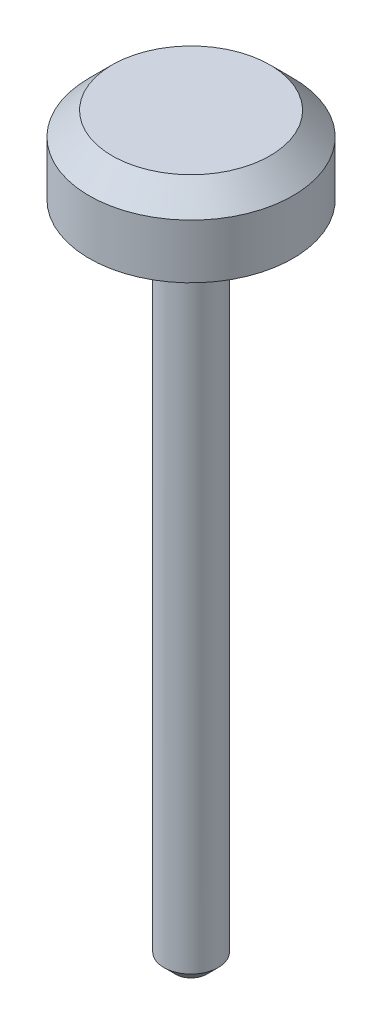
SolidWorks part; units mm, degrees
ref_plane "Front Plane" through (0, 0, 0) normal (0, 0, 1) x (1, 0, 0)
ref_plane "Top Plane" through (0, 0, 0) normal (0, 1, 0) x (1, 0, 0)
ref_plane "Right Plane" through (0, 0, 0) normal (1, 0, 0) x (0, 0, -1)
sketch "Sketch2" plane through (0, 0, 0) normal (0, 0, 1) x (1, 0, 0)
  line L0 (0, 22.3138) -> (0, -62.2714) construction
  line L1 (0, 22.3138) -> (-7.2649, 22.3138)
  line L2 (-7.2649, 22.3138) -> (-9.3862, 20.1925)
  line L3 (-9.3862, 20.1925) -> (-9.3862, 15.1925)
  line L4 (-9.3862, 15.1925) -> (-2.5, 15.1925)
  line L5 (-2.5, 15.1925) -> (-2.5, -44.8075)
  line L6 (-2.5, -44.8075) -> (-1.4393, -45.8682)
  line L7 (-1.4393, -45.8682) -> (0, -45.8682)
  line L8 (0, -45.8682) -> (0, 22.3138)
  dimension "D1" = 60
  dimension "D2" = 1.5
  dimension "D3" = 2.5
  dimension "D4" = 5
  dimension "D5" = 3
revolve "Revolve1" add sketch "Sketch2" angle 360 about L0
chamfer "Chamfer3" distance 1 angle 45 1 edges at (-2.5, 15.1925, 0)
